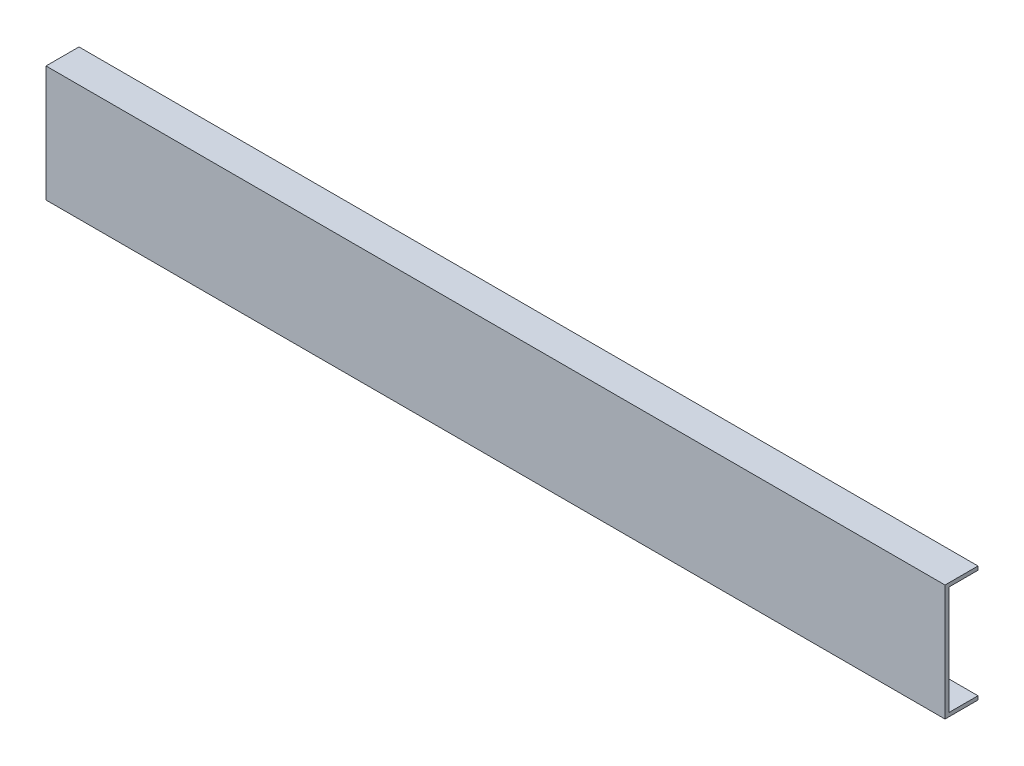
SolidWorks part; units mm, degrees
ref_plane "Front Plane" through (0, 0, 0) normal (0, 0, 1) x (1, 0, 0)
ref_plane "Top Plane" through (0, 0, 0) normal (0, 1, 0) x (1, 0, 0)
ref_plane "Right Plane" through (0, 0, 0) normal (1, 0, 0) x (0, 0, -1)
sketch "Sketch2" plane through (0, 0, 0) normal (0, 0, 1) x (1, 0, 0)
  line L1 (0, 0) -> (609.6, 0)
  line L2 (0, 0) -> (0, 78.74)
  line L3 (0, 78.74) -> (609.6, 78.74)
  line L4 (609.6, 0) -> (609.6, 78.74)
  dimension "D1" = 78.74
  dimension "D2" = 609.6
extrude "Boss-Extrude1" add sketch "Sketch2" along normal blind 22.352
sketch "Sketch3" plane through (609.6, 0, 0) normal (1, 0, 0) x (0, 0, -1)
  line L0 (0, 0) -> (0, 78.74) construction
  line L1 (0, 76.2) -> (-19.812, 76.2)
  line L2 (0, 76.2) -> (0, 2.54)
  line L3 (0, 2.54) -> (-19.812, 2.54)
  line L4 (-19.812, 76.2) -> (-19.812, 2.54)
  line L5 (-22.352, 0) -> (-22.352, 78.74) construction
  line L6 (-22.352, 78.74) -> (0, 78.74) construction
  line L7 (-22.352, 0) -> (0, 0) construction
  dimension "D1" = 2.54
  dimension "D2" = 2.54
  dimension "D3" = 2.54
extrude "Cut-Extrude1" cut sketch "Sketch3" against normal through all
